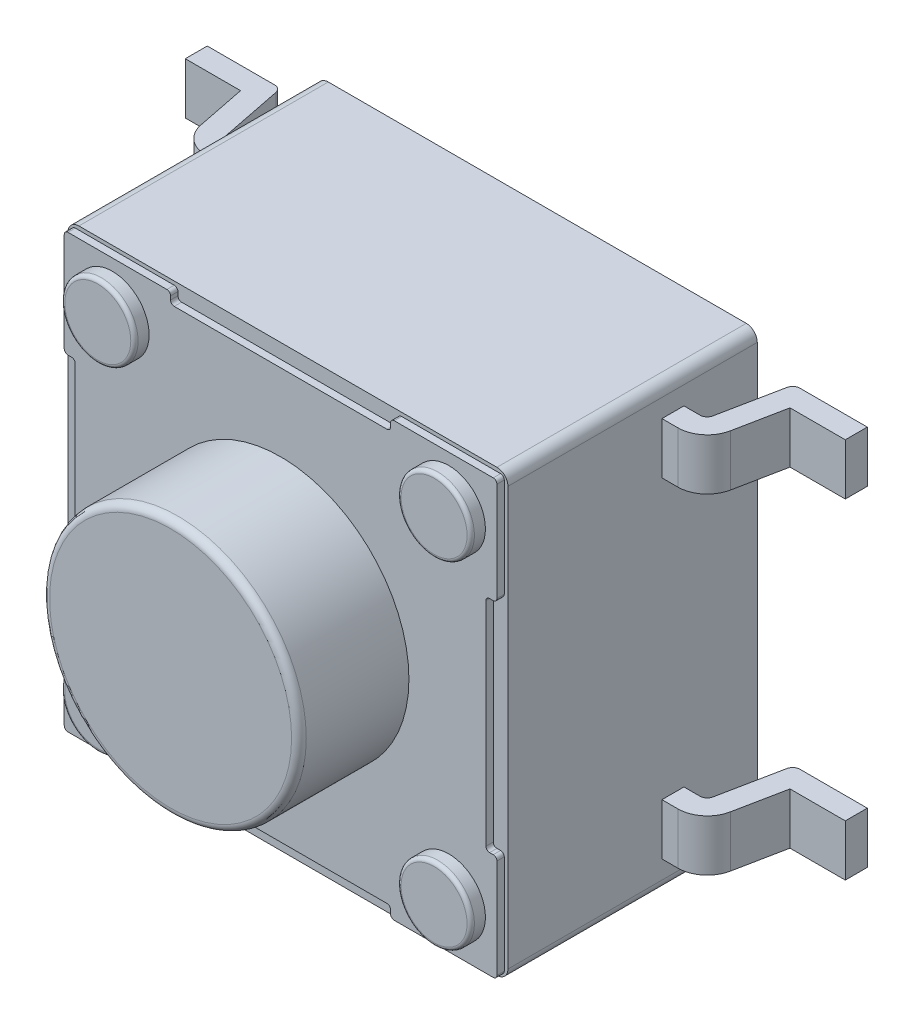
SolidWorks part; units mm, degrees
ref_plane "Front" through (0, 0, 0) normal (0, 0, 1) x (1, 0, 0)
ref_plane "Top" through (0, 0, 0) normal (0, 1, 0) x (1, 0, 0)
ref_plane "Right" through (0, 0, 0) normal (1, 0, 0) x (0, 0, -1)
sketch "Sketch1" plane through (0, 0, 0) normal (0, 0, 1) x (1, 0, 0)
  line L0 (0, 20.4576) -> (0, -20.4576) construction
  line L1 (-26.763, 0) -> (26.763, 0) construction
  line L2 (0, 0) -> (3, 3) construction
  line L3 (-3, 3) -> (3, 3)
  line L4 (-3, 3) -> (-3, -3)
  line L5 (-3, -3) -> (3, -3)
  line L6 (3, 3) -> (3, -3)
  line L7 (-1.5, 3) -> (-1.5, 2.8) construction
  line L8 (-1.5, 2.8) -> (1.5, 2.8) construction
  line L9 (1.5, 2.8) -> (1.5, 3) construction
  circle A0 centre (0, 0) radius 1.75 construction
  circle A1 centre (2.2929, 2.2929) radius 0.5 construction
  circle A2 centre (-2.2929, 2.2929) radius 0.5 construction
  circle A3 centre (-2.2929, -2.2929) radius 0.5 construction
  circle A4 centre (2.2929, -2.2929) radius 0.5 construction
  dimension "D2" = 3.5
  dimension "D3" = 1
  dimension "D1" = 6
  dimension "D4" = 1
  dimension "D5" = 3
  dimension "D6" = 0.2
extrude "Base-Extrude" add sketch "Sketch1" along normal blind 3.4
sketch "Sketch2" plane through (0, 0, 3.4) normal (0, 0, 1) x (1, 0, 0)
  line L0 (2.95, 1.5) -> (2.8, 1.5)
  line L1 (2.8, 1.5) -> (2.8, -1.5)
  line L2 (2.8, -1.5) -> (2.95, -1.5)
  line L3 (1.5, -2.95) -> (1.5, -2.8)
  line L4 (-1.5, 3) -> (-1.5, 2.8) construction
  line L5 (-1.5, 2.8) -> (1.5, 2.8) construction
  line L6 (1.5, 2.8) -> (1.5, 3) construction
  line L7 (-1.5, 2.95) -> (-1.5, 2.8)
  line L8 (2.95, 2.95) -> (-2.95, 2.95)
  line L9 (-2.95, 2.95) -> (-2.95, -2.95)
  line L10 (-2.95, -2.95) -> (2.95, -2.95)
  line L11 (2.95, -2.95) -> (2.95, 2.95)
  line L12 (2.95, 2.95) -> (1.5, 2.95)
  line L13 (-2.95, 2.95) -> (-2.95, -2.95)
  line L14 (-2.95, -2.95) -> (2.95, -2.95)
  line L15 (2.95, -2.95) -> (2.95, 2.95)
  line L16 (-1.5, 2.8) -> (1.5, 2.8)
  line L17 (1.5, 2.8) -> (1.5, 2.95)
  line L18 (-1.5, 2.95) -> (-2.95, 2.95)
  line L19 (1.5, -2.8) -> (-1.5, -2.8)
  line L20 (-1.5, -2.8) -> (-1.5, -2.95)
  line L21 (-2.95, -1.5) -> (-2.8, -1.5)
  line L22 (-2.8, -1.5) -> (-2.8, 1.5)
  line L23 (-2.8, 1.5) -> (-2.95, 1.5)
  line L24 (0, 0) -> (1.5, 2.8) construction
  dimension "D2" = 3.1765
  dimension "D1" = 0.05
sketch "Sketch3" plane through (0, 0, 3.4) normal (0, 0, 1) x (1, 0, 0)
  line L0 (2.95, 2.95) -> (1.5, 2.95) construction
  line L1 (1.5, 2.8) -> (1.5, 2.95) construction
  line L2 (-1.5, 2.8) -> (1.5, 2.8) construction
  line L3 (-1.5, 2.95) -> (-1.5, 2.8) construction
  line L4 (-2.8, 1.5) -> (-2.95, 1.5) construction
  line L5 (-2.8, -1.5) -> (-2.8, 1.5) construction
  line L6 (-2.95, 2.95) -> (-2.95, -2.95) construction
  line L7 (-1.5, 2.95) -> (-2.95, 2.95) construction
  line L8 (2.9, 2.95) -> (1.55, 2.95)
  line L9 (1.5, 2.85) -> (1.5, 2.9)
  line L10 (-1.45, 2.8) -> (1.45, 2.8)
  line L11 (-1.5, 2.9) -> (-1.5, 2.85)
  line L12 (-2.85, 1.5) -> (-2.9, 1.5)
  line L13 (-2.8, -1.45) -> (-2.8, 1.45)
  line L14 (-2.95, 2.9) -> (-2.95, 1.55)
  line L15 (-1.55, 2.95) -> (-2.9, 2.95)
  line L16 (2.8, 1.5) -> (2.8, -1.5) construction
  line L17 (2.95, -2.95) -> (2.95, 2.95) construction
  line L18 (2.8, 1.45) -> (2.8, -1.45)
  line L19 (2.95, -2.9) -> (2.95, -1.55)
  line L20 (2.8, -1.5) -> (2.95, -1.5) construction
  line L21 (2.95, 1.5) -> (2.8, 1.5) construction
  line L22 (2.85, -1.5) -> (2.9, -1.5)
  line L23 (2.9, 1.5) -> (2.85, 1.5)
  line L24 (-1.5, -2.8) -> (-1.5, -2.95) construction
  line L25 (1.5, -2.8) -> (-1.5, -2.8) construction
  line L26 (1.5, -2.95) -> (1.5, -2.8) construction
  line L27 (-2.95, -2.95) -> (2.95, -2.95) construction
  line L28 (-1.5, -2.85) -> (-1.5, -2.9)
  line L29 (1.45, -2.8) -> (-1.45, -2.8)
  line L30 (1.5, -2.9) -> (1.5, -2.85)
  line L31 (-2.9, -2.95) -> (-1.55, -2.95)
  line L32 (2.95, 1.55) -> (2.95, 2.9)
  line L33 (1.55, -2.95) -> (2.9, -2.95)
  line L34 (-2.95, -1.5) -> (-2.8, -1.5) construction
  line L35 (-2.9, -1.5) -> (-2.85, -1.5)
  line L36 (-2.95, -1.55) -> (-2.95, -2.9)
  arc A0 (2.8, 1.45) -> (2.85, 1.5) centre (2.85, 1.45) cw
  arc A1 (2.9, 1.5) -> (2.95, 1.55) centre (2.9, 1.55) ccw
  arc A2 (2.9, -1.5) -> (2.95, -1.55) centre (2.9, -1.55) cw
  arc A3 (2.8, -1.45) -> (2.85, -1.5) centre (2.85, -1.45) ccw
  arc A4 (1.5, -2.9) -> (1.55, -2.95) centre (1.55, -2.9) ccw
  arc A5 (1.45, -2.8) -> (1.5, -2.85) centre (1.45, -2.85) cw
  arc A6 (-1.5, -2.9) -> (-1.55, -2.95) centre (-1.55, -2.9) cw
  arc A7 (-1.5, -2.85) -> (-1.45, -2.8) centre (-1.45, -2.85) cw
  arc A8 (1.5, 2.85) -> (1.45, 2.8) centre (1.45, 2.85) cw
  arc A9 (1.55, 2.95) -> (1.5, 2.9) centre (1.55, 2.9) ccw
  arc A10 (-1.45, 2.8) -> (-1.5, 2.85) centre (-1.45, 2.85) cw
  arc A11 (-1.5, 2.9) -> (-1.55, 2.95) centre (-1.55, 2.9) ccw
  arc A12 (-2.95, 2.9) -> (-2.9, 2.95) centre (-2.9, 2.9) cw
  arc A13 (-2.9, 1.5) -> (-2.95, 1.55) centre (-2.9, 1.55) cw
  arc A14 (-2.85, 1.5) -> (-2.8, 1.45) centre (-2.85, 1.45) cw
  arc A15 (2.95, -2.9) -> (2.9, -2.95) centre (2.9, -2.9) cw
  arc A16 (2.9, 2.95) -> (2.95, 2.9) centre (2.9, 2.9) cw
  arc A17 (-2.95, -2.9) -> (-2.9, -2.95) centre (-2.9, -2.9) ccw
  arc A18 (-2.9, -1.5) -> (-2.95, -1.55) centre (-2.9, -1.55) ccw
  arc A19 (-2.8, -1.45) -> (-2.85, -1.5) centre (-2.85, -1.45) cw
  dimension "D1" = 0.05
  dimension "D2" = 0.05
extrude "Boss-Extrude1" add sketch "Sketch3" along normal offset from surface (0.1 mm away) 3.5 up to face at (0, 0, 0)
sketch "Sketch4" plane through (0, 0, 3.5) normal (0, 0, 1) x (1, 0, 0)
  circle A0 centre (0, 0) radius 1.75 construction
  circle A1 centre (0, 0) radius 1.75
extrude "Boss-Extrude2" add sketch "Sketch4" along normal offset from surface (1.5 mm away) 5
fillet "Fillet1" radius 0.1 1 edges at (1.75, 0, 5)
sketch "Sketch5" plane through (0, 0, 3.5) normal (0, 0, 1) x (1, 0, 0)
  circle A0 centre (2.2929, -2.2929) radius 0.5 construction
  circle A1 centre (-2.2929, -2.2929) radius 0.5 construction
  circle A2 centre (-2.2929, 2.2929) radius 0.5 construction
  circle A3 centre (2.2929, 2.2929) radius 0.5 construction
  circle A4 centre (2.2929, -2.2929) radius 0.5
  circle A5 centre (-2.2929, -2.2929) radius 0.5
  circle A6 centre (-2.2929, 2.2929) radius 0.5
  circle A7 centre (2.2929, 2.2929) radius 0.5
extrude "Boss-Extrude3" add sketch "Sketch5" along normal blind 0.2
fillet "Fillet2" radius 0.05 4 edges at (-1.7929, 2.2929, 3.7) (-1.7929, -2.2929, 3.7) (2.7929, 2.2929, 3.7) (2.7929, -2.2929, 3.7)
ref_plane "Plane1" through (0, -2.25, 0) normal (0, 1, 0) x (-1, 0, 0)
sketch "Sketch6" plane through (0, -2.25, 0) normal (0, 1, 0) x (-1, 0, 0)
  line L0 (-3, 1) -> (-3.218, 1)
  line L1 (-3, 3.4) -> (-3, 0) construction
  line L2 (-3.582, 0) -> (-4.5, 0)
  line L4 (-3.3161, 0.9196) -> (-3.4839, 0.0804)
  line L5 (3, 0) -> (-3, 0) construction
  line L6 (0, 0) -> (0, 1.0284) construction
  line L7 (0, 4.9) -> (0, 3.5) construction
  line L8 (-3.7459, 0.3) -> (-4.5, 0.3)
  line L9 (-3.6103, 0.9784) -> (-3.7459, 0.3)
  line L10 (-3, 1.3) -> (-3.218, 1.3)
  line L11 (-3, 1.3) -> (-3, 1)
  line L12 (-4.5, 0.3) -> (-4.5, 0)
  arc A0 (-3.4839, 0.0804) -> (-3.582, 0) centre (-3.582, 0.1) cw
  arc A1 (-3.218, 1) -> (-3.3161, 0.9196) centre (-3.218, 0.9) ccw
  arc A2 (-3.218, 1.3) -> (-3.6103, 0.9784) centre (-3.218, 0.9) ccw
  point P15 (-3.5, 0)
  point P18 (-3.3, 1)
  dimension "D5" = 0.1
  dimension "D6" = 0.1
  dimension "D1" = 0.3
  dimension "D2" = 1
  dimension "D3" = 9
  dimension "D4" = 1
  dimension "D7" = 0.3
extrude "Boss-Extrude4" add sketch "Sketch6" along normal mid plane 0.7
mirror "Mirror1" about plane through (0, 0, 0) normal (0, 1, 0) of "Boss-Extrude4"
mirror "Mirror2" about plane through (0, 0, 0) normal (1, 0, 0) of "Mirror1", "Boss-Extrude4"
fillet "Fillet3" radius 0.15 4 edges at (-3, 3, 1.7) (3, 3, 1.7) (3, -3, 1.7) (-3, -3, 1.7)
sketch "Place Sketch" plane through (0, 0, 0) normal (0, 0, -1) x (-1, 0, 0)
  line L0 (0, 3) -> (0, -3) construction
  line L1 (2.85, -3) -> (-2.85, -3) construction
  line L2 (-2.85, 3) -> (2.85, 3) construction
  line L3 (-3, 0) -> (3, 0) construction
  line L4 (-3, -2.85) -> (-3, 2.85) construction
  line L5 (3, 2.85) -> (3, -2.85) construction
